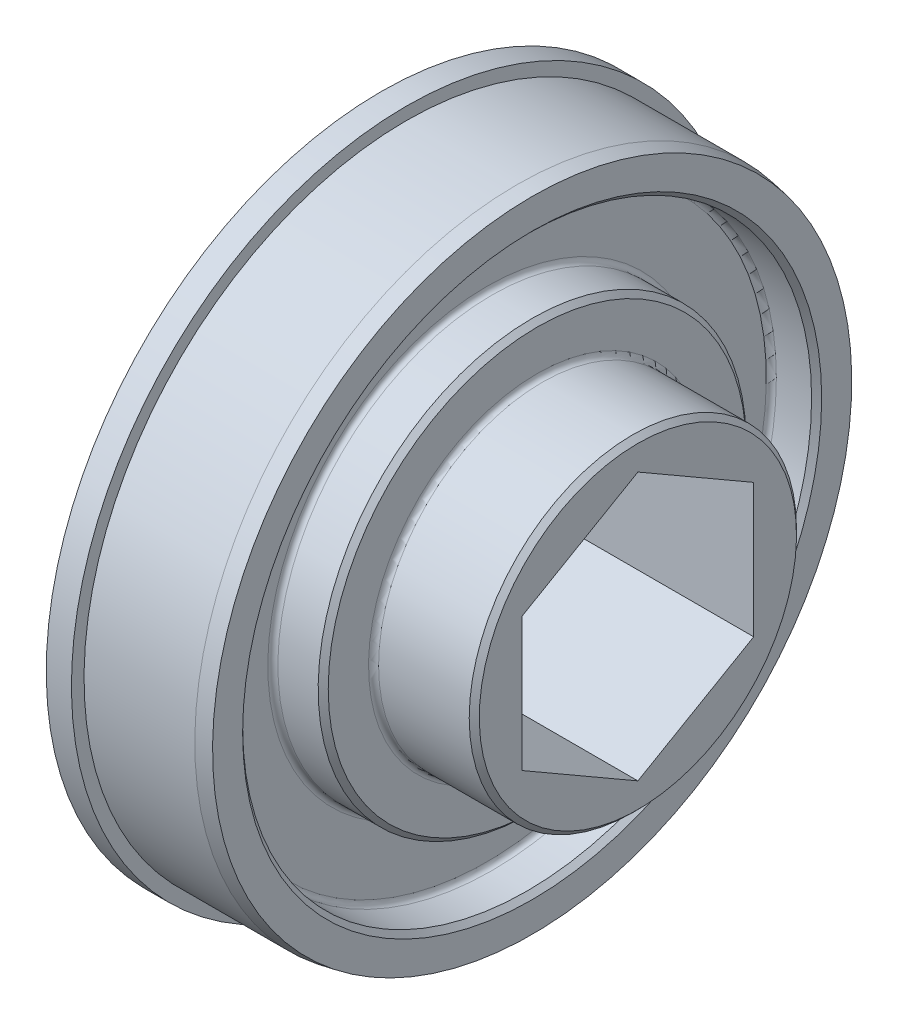
SolidWorks part; units mm, degrees
material "Сталь 20 ГОСТ 1050-2013"
ref_plane "Спереди" through (0, 0, 0) normal (0, 0, 1) x (1, 0, 0)
ref_plane "Сверху" through (0, 0, 0) normal (0, 1, 0) x (1, 0, 0)
ref_plane "Справа" through (0, 0, 0) normal (1, 0, 0) x (0, 0, -1)
sketch "Эскиз1" plane through (0, 0, 0) normal (0, 0, 1) x (1, 0, 0)
  line L0 (0, 0) -> (-72, 0) construction
  line L1 (0, 0) -> (-57, 0)
  line L2 (-57, 0) -> (-57, 27.5)
  line L3 (-57, 27.5) -> (-72, 27.5)
  line L4 (-72, 27.5) -> (-72, 31.5)
  line L5 (-71, 32.5) -> (-53, 32.5)
  line L6 (-52, 33.5) -> (-52, 41.5)
  line L7 (-51, 42.5) -> (-43, 42.5)
  line L8 (-42, 43.5) -> (-42, 55.5)
  line L9 (-43, 56.5) -> (-50, 56.5)
  line L10 (-51, 57.5) -> (-51, 66.5)
  line L11 (-51, 66.5) -> (-46, 66.5)
  line L12 (-46, 66.5) -> (-46, 64)
  line L13 (-46, 64) -> (-24, 64)
  line L14 (-24, 64) -> (-21, 63.471)
  line L15 (-21, 63.471) -> (-21, 57.5)
  line L16 (-22, 56.5) -> (-29, 56.5)
  line L17 (-30, 55.5) -> (-30, 43.5)
  line L18 (-29, 42.5) -> (-21, 42.5)
  line L19 (-20, 41.5) -> (-20, 33.5)
  line L20 (-19, 32.5) -> (-1, 32.5)
  line L21 (0, 31.5) -> (0, 0)
  line L22 (-72, 31.5) -> (-71, 32.5)
  line L23 (-50, 56.5) -> (-51, 57.5)
  line L24 (-21, 57.5) -> (-22, 56.5)
  line L25 (-21, 42.5) -> (-20, 41.5)
  line L26 (-52, 41.5) -> (-51, 42.5)
  line L27 (-1, 32.5) -> (0, 31.5)
  arc A0 (-43, 42.5) -> (-42, 43.5) centre (-43, 43.5) ccw
  arc A1 (-42, 55.5) -> (-43, 56.5) centre (-43, 55.5) ccw
  arc A2 (-29, 56.5) -> (-30, 55.5) centre (-29, 55.5) ccw
  arc A3 (-30, 43.5) -> (-29, 42.5) centre (-29, 43.5) ccw
  arc A4 (-20, 33.5) -> (-19, 32.5) centre (-19, 33.5) ccw
  arc A5 (-53, 32.5) -> (-52, 33.5) centre (-53, 33.5) ccw
  point P7 (-72, 32.5)
  point P9 (-52, 42.5)
  point P12 (-51, 56.5)
  point P18 (-21, 56.5)
  point P21 (-20, 42.5)
  point P23 (0, 32.5)
  point P31 (-30, 56.5)
  dimension "D21" = 1
  dimension "D1" = 65
  dimension "D2" = 55
  dimension "D3" = 65
  dimension "D4" = 15
  dimension "D5" = 72
  dimension "D6" = 9
  dimension "D7" = 1
  dimension "D8" = 12
  dimension "D9" = 30
  dimension "D10" = 32
  dimension "D11" = 85
  dimension "D12" = 113
  dimension "D13" = 133
  dimension "D14" = 128
  dimension "D15" = 3
  dimension "D16" = 10
  dimension "D17" = 20
  dimension "D18" = 25
  dimension "D19" = 1
  dimension "D20" = 45
  dimension "D22" = 1
  dimension "D23" = 45
  dimension "D24" = 1
  dimension "D25" = 45
  dimension "D26" = 1
  dimension "D27" = 45
  dimension "D28" = 1
  dimension "D29" = 45
  dimension "D30" = 1
  dimension "D31" = 45
revolve "Повернуть1" add sketch "Эскиз1" angle 360 about L0
sketch "Эскиз2" plane through (0, 0, 0) normal (1, 0, 0) x (0, 0, -1)
  line L1 (0, 26.5581) -> (-23, 13.2791)
  line L2 (-23, 13.2791) -> (-23, -13.2791)
  line L3 (-23, -13.2791) -> (0, -26.5581)
  line L4 (0, -26.5581) -> (23, -13.2791)
  line L5 (23, -13.2791) -> (23, 13.2791)
  line L6 (23, 13.2791) -> (0, 26.5581)
  circle A0 centre (0, 0) radius 23 construction
  dimension "D1" = 46
extrude "Вырез-Вытянуть1" cut sketch "Эскиз2" against normal through all
